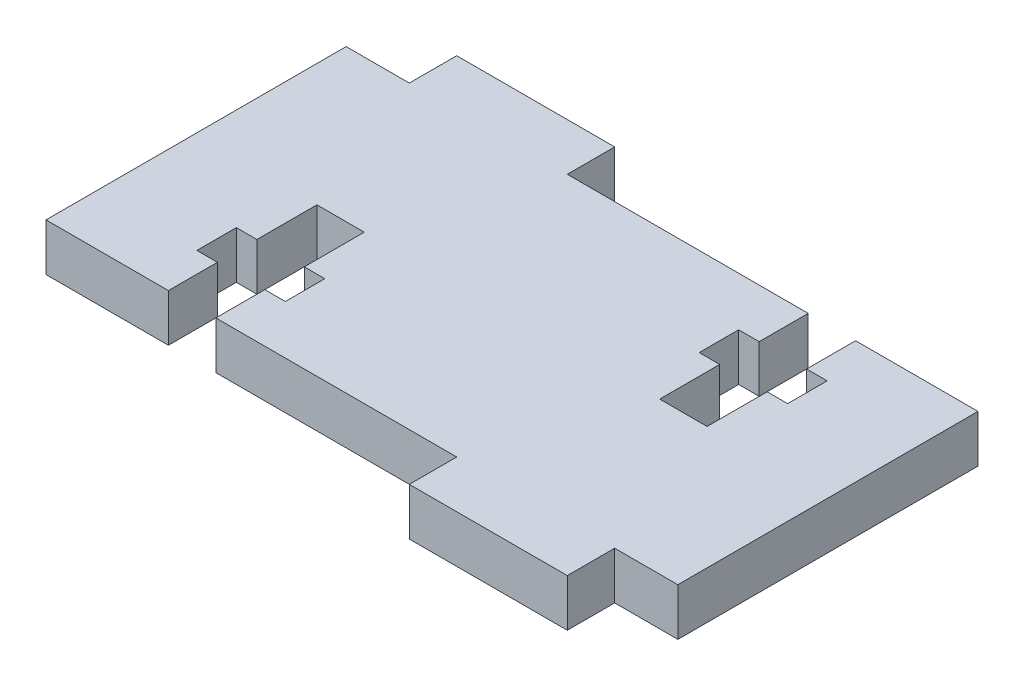
SolidWorks part; units mm, degrees
ref_plane "Front Plane" through (0, 0, 0) normal (0, 0, 1) x (1, 0, 0)
ref_plane "Top Plane" through (0, 0, 0) normal (0, 1, 0) x (1, 0, 0)
ref_plane "Right Plane" through (0, 0, 0) normal (1, 0, 0) x (0, 0, -1)
sketch "Sketch2" plane through (0, 0, 0) normal (0, 1, 0) x (1, 0, 0)
  line L1 (0, 0) -> (-4, 0)
  line L2 (0, 0) -> (0, 19)
  line L3 (0, 19) -> (-7.75, 19)
  line L4 (-40, 0) -> (-40, 19)
  line L5 (0, 9.5) -> (-40, 9.5) construction
  line L6 (-4, 0) -> (-4, -3)
  line L7 (-4, -3) -> (-14, -3)
  line L8 (-14, -3) -> (-14, 0)
  line L9 (-14, 0) -> (-29.25, 0)
  line L10 (-29.25, 0) -> (-29.25, 3.1)
  line L11 (-29.25, 3.1) -> (-27.95, 3.1)
  line L12 (-27.95, 3.1) -> (-27.95, 5.6)
  line L13 (-27.95, 5.6) -> (-29.25, 5.6)
  line L14 (-29.25, 5.6) -> (-29.25, 9.4)
  line L15 (-29.25, 9.4) -> (-32.25, 9.4)
  line L16 (-32.25, 9.4) -> (-32.25, 5.6)
  line L17 (-32.25, 5.6) -> (-33.55, 5.6)
  line L18 (-33.55, 5.6) -> (-33.55, 3.1)
  line L19 (-33.55, 3.1) -> (-32.25, 3.1)
  line L20 (-32.25, 3.1) -> (-32.25, 0)
  line L21 (-32.25, 0) -> (-40, 0)
  line L26 (-7.75, 19) -> (-7.75, 15.9)
  line L27 (-26, 19) -> (-26, 22)
  line L28 (-26, 22) -> (-36, 22)
  line L29 (-36, 22) -> (-36, 19)
  line L30 (-36, 19) -> (-40, 19)
  line L31 (-7.75, 15.9) -> (-6.45, 15.9)
  line L32 (-6.45, 15.9) -> (-6.45, 13.4)
  line L33 (-6.45, 13.4) -> (-7.75, 13.4)
  line L34 (-7.75, 13.4) -> (-7.75, 9.6)
  line L35 (-7.75, 9.6) -> (-10.75, 9.6)
  line L36 (-10.75, 9.6) -> (-10.75, 13.4)
  line L37 (-10.75, 13.4) -> (-12.05, 13.4)
  line L38 (-12.05, 13.4) -> (-12.05, 15.9)
  line L39 (-12.05, 15.9) -> (-10.75, 15.9)
  line L40 (-10.75, 15.9) -> (-10.75, 19)
  line L41 (-10.75, 19) -> (-26, 19)
  point P5 (-4, 0)
  point P6 (-7.75, 19)
  point P7 (0, 0)
  point P21 (-39.55, 0)
  point P28 (-39.4045, 21.5)
  dimension "D1" = 40
  dimension "D2" = 19
  dimension "D3" = 4
  dimension "D4" = 10
  dimension "D5" = 3.1
  dimension "D6" = 2.5
  dimension "D7" = 3.8
  dimension "D8" = 3
  dimension "D9" = 1.3
  dimension "D10" = 3
  dimension "D11" = 7.75
  dimension "D12" = 7.75
  dimension "D13" = 4
extrude "Boss-Extrude2" add sketch "Sketch2" along normal blind 3
